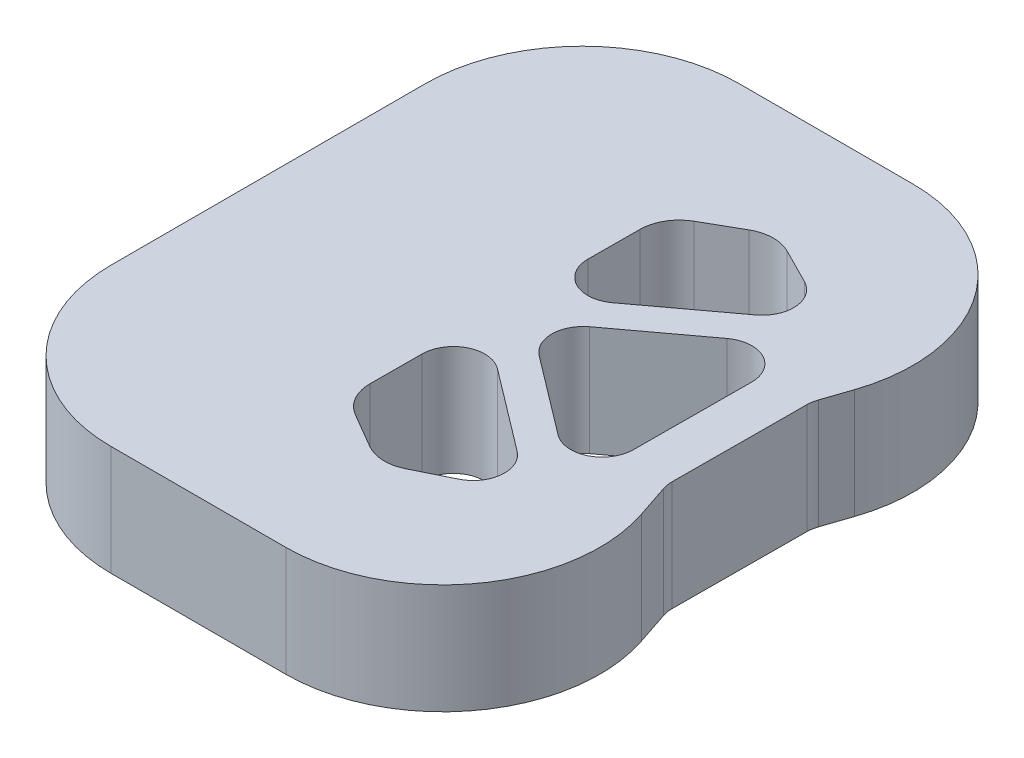
SolidWorks part; units mm, degrees
material "ABS"
ref_plane "Front Plane" through (0, 0, 0) normal (0, 0, 1) x (1, 0, 0)
ref_plane "Top Plane" through (0, 0, 0) normal (0, 1, 0) x (1, 0, 0)
ref_plane "Right Plane" through (0, 0, 0) normal (1, 0, 0) x (0, 0, -1)
sketch "Sketch1" plane through (0, 0, 0) normal (0, 1, 0) x (1, 0, 0)
  line L1 (-17.5, -20) -> (17.5, -20)
  line L2 (-17.5, -20) -> (-17.5, 20)
  line L3 (-17.5, 20) -> (17.5, 20)
  line L4 (17.5, -20) -> (17.5, 20)
  line L5 (-17.5, -20) -> (17.5, 20) construction
  line L6 (-17.5, 20) -> (17.5, -20) construction
  point P0 (0, 0)
  dimension "D1" = 40
  dimension "D2" = 35
extrude "Boss-Extrude1" add sketch "Sketch1" along normal blind 7
sketch "Sketch2" plane through (0, 7, 0) normal (0, 1, 0) x (1, 0, 0)
  line L14 (22.8647, 2.3683) -> (15.2501, 6.2224)
  line L15 (22.8428, -2.1037) -> (15.1908, -5.883)
  line L16 (12.3469, 4.4478) -> (12.3052, -4.08)
  line L17 (5.4847, 11.1645) -> (3.2289, 12.3063)
  line L18 (0.5435, 3.8914) -> (5.7737, 7.7742)
  line L19 (0.8605, 12.2469) -> (-1.3719, 10.9726)
  line L20 (-2.6325, 8.8137) -> (-2.6487, 5.5071)
  line L21 (1.1177, -1.3615) -> (6.0993, -5.1359)
  line L22 (1.1334, 1.8385) -> (6.1517, 5.564)
  line L23 (9.3439, 3.9483) -> (9.3071, -3.5516)
  line L24 (-2.7001, -4.9928) -> (-2.7163, -8.2994)
  line L25 (0.7429, -11.7667) -> (-1.4769, -10.4705)
  line L26 (5.3775, -10.7296) -> (3.1105, -11.8493)
  line L27 (0.5077, -3.4085) -> (5.6997, -7.3423)
  line L28 (17.5, -20) -> (11.7843, -2.8517)
  line L29 (17.5, 20) -> (11.7357, 2.9603)
  line L32 (17.5, -20) -> (17.5, 20)
  line L33 (17.5, 20) -> (-17.5, 20)
  line L34 (-17.5, 20) -> (-17.5, -20)
  line L35 (-17.5, -20) -> (17.5, -20)
  line L36 (17.5, -20) -> (17.5, 20)
  line L37 (17.5, 20) -> (-17.5, 20)
  line L38 (-17.5, 20) -> (-17.5, -20)
  line L39 (-17.5, -20) -> (17.5, -20)
  arc A14 (22.8428, -2.1037) -> (22.8647, 2.3683) centre (21.7358, 0.1378) ccw
  arc A15 (12.3052, -4.08) -> (15.1908, -5.883) centre (14.3051, -4.0898) ccw
  arc A16 (15.2501, 6.2224) -> (12.3469, 4.4478) centre (14.3469, 4.438) ccw
  arc A17 (5.7737, 7.7742) -> (5.4847, 11.1645) centre (4.5815, 9.3801) ccw
  arc A18 (3.2289, 12.3063) -> (0.8605, 12.2469) centre (2.0999, 10.0757) ccw
  arc A19 (-1.3719, 10.9726) -> (-2.6325, 8.8137) centre (-0.1325, 8.8014) ccw
  arc A20 (-2.6487, 5.5071) -> (0.5435, 3.8914) centre (-0.6487, 5.4973) ccw
  arc A21 (1.1334, 1.8385) -> (1.1177, -1.3615) centre (2.3256, 0.2327) ccw
  arc A22 (9.3439, 3.9483) -> (6.1517, 5.564) centre (7.3439, 3.9581) ccw
  arc A23 (6.0993, -5.1359) -> (9.3071, -3.5516) centre (7.3071, -3.5418) ccw
  arc A24 (-2.7163, -8.2994) -> (-1.4769, -10.4705) centre (-0.2163, -8.3116) ccw
  arc A25 (0.7429, -11.7667) -> (3.1105, -11.8493) centre (2.0035, -9.6078) ccw
  arc A26 (5.3775, -10.7296) -> (5.6997, -7.3423) centre (4.4918, -8.9364) ccw
  arc A27 (0.5077, -3.4085) -> (-2.7001, -4.9928) centre (-0.7001, -5.0026) ccw
  line M12 (17.5, -20) -> (17.5, 20)
  dimension "D1" = 0
extrude "Cut-Extrude1" cut sketch "Sketch2" against normal blind 8 contours A16 L14 L29 M12 | L14 A16 L16 A15 L15 M12 | A15 L28 L15 M12 | L21 A23 L23 A22 L22 A21 | L20 A20 L18 A17 L17 A18 L19 A19 | L27 A27 L24 A24 L25 A25 L26 A26
fillet "Fillet1" radius 10 4 edges at (17.5, 3.5, -20) (17.5, 3.5, 20) (-17.5, 3.5, 20) (-17.5, 3.5, -20)
